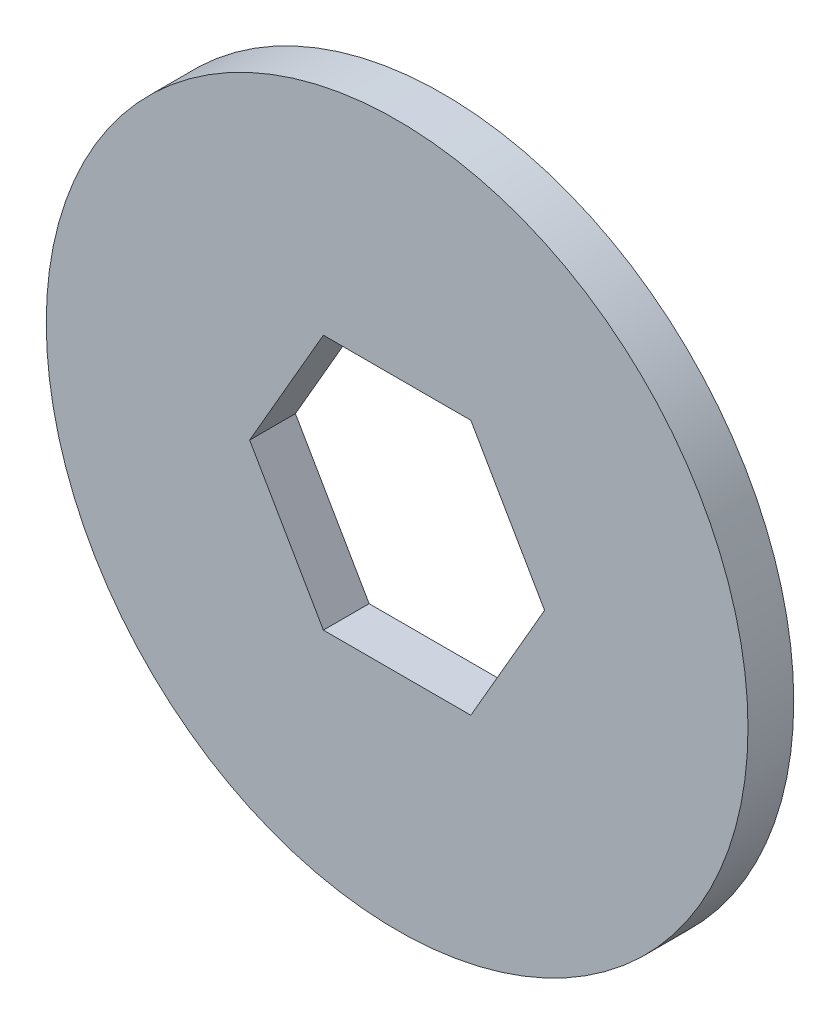
SolidWorks part; units mm, degrees
material "Rubber"
ref_plane "Front Plane" through (0, 0, 0) normal (0, 0, 1) x (1, 0, 0)
ref_plane "Top Plane" through (0, 0, 0) normal (0, 1, 0) x (1, 0, 0)
ref_plane "Right Plane" through (0, 0, 0) normal (1, 0, 0) x (0, 0, -1)
sketch "Sketch1" plane through (0, 0, 0) normal (0, 0, 1) x (1, 0, 0)
  circle A0 centre (0, 0) radius 17.526
  dimension "D1" = 35.052
extrude "Boss-Extrude1" add sketch "Sketch1" along normal blind 2.286
sketch "Sketch2" plane through (0, 0, 0) normal (0, 0, -1) x (-1, 0, 0)
  line L0 (0, 0) -> (7.366, 0) construction
  line L1 (3.683, 6.3791) -> (-3.683, 6.3791)
  line L2 (-3.683, 6.3791) -> (-7.366, 0)
  line L3 (-7.366, 0) -> (-3.683, -6.3791)
  line L4 (-3.683, -6.3791) -> (3.683, -6.3791)
  line L5 (3.683, -6.3791) -> (7.366, 0)
  line L6 (7.366, 0) -> (3.683, 6.3791)
  circle A0 centre (0, 0) radius 6.3791 construction
  dimension "D1" = 7.366
extrude "Cut-Extrude1" cut sketch "Sketch2" against normal through all both and the other way through all
